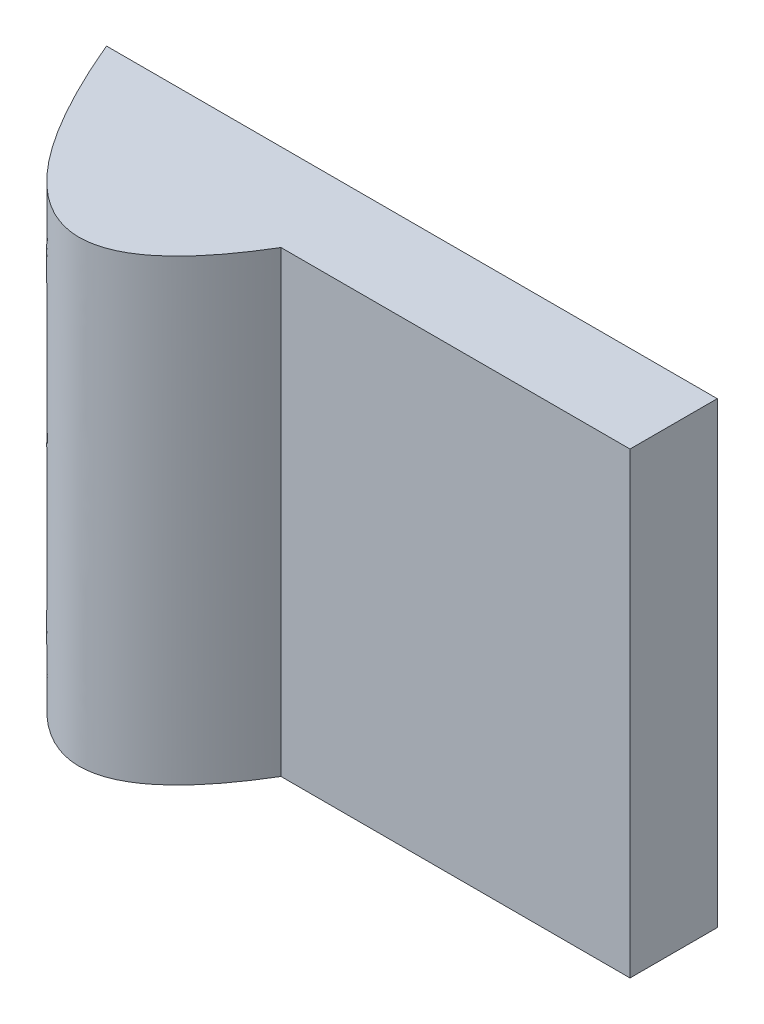
SolidWorks part; units mm, degrees
ref_plane "Alzado" through (0, 0, 0) normal (0, 0, 1) x (1, 0, 0)
ref_plane "Planta" through (0, 0, 0) normal (0, 1, 0) x (1, 0, 0)
ref_plane "Vista lateral" through (0, 0, 0) normal (1, 0, 0) x (0, 0, -1)
sketch "Croquis2" plane through (0, 0, 0) normal (0, 1, 0) x (1, 0, 0)
  line L0 (-200, 70) -> (200, 70)
  line L1 (-200, 70) -> (-200, -70)
  line L2 (-200, -70) -> (200, -70)
  line L3 (200, 70) -> (200, -70)
  line L4 (0, 70) -> (60, 70)
  line L5 (0, 70) -> (0, -70)
  line L6 (0, -70) -> (60, -70)
  line L7 (60, 70) -> (60, -70)
  line L8 (200, 70) -> (120, 70)
  line L9 (200, 70) -> (200, 50)
  line L10 (200, 50) -> (120, 50)
  line L11 (0, 70) -> (-60, 70)
  line L12 (0, 70) -> (0, 50)
  line L13 (0, 50) -> (-60, 50)
  line L14 (-60, 60.1561) -> (-60, 50)
  spline S0 degree 2 poles (60, 70) (89.7639, -0.5628) (120, 50) knots 0 0 0 1 1 1
  spline S1 degree 2 poles (-120, 70) (-89.7132, -0.7337) (-60, 50) knots 0 0 0 1 1 1
  point P14 (99.6856, 29.6804)
  point P15 (60, 70)
  point P16 (120, 50)
  point P18 (-120, 70)
  point P19 (-60, 50)
  point P20 (-79.8536, 29.6804)
extrude "Saliente-Extruir1" add sketch "Croquis2" along normal blind 105 contours L0 S0 L10 L3
sketch "Croquis4" plane through (0, 105, 0) normal (0, 1, 0) x (1, 0, 0)
  line L6 (197.5, 67.5) -> (63.8008, 67.5)
  line L7 (118.5717, 52.5) -> (197.5, 52.5)
  line L8 (197.5, 52.5) -> (197.5, 67.5)
  line L9 (197.5, 67.5) -> (63.8008, 67.5)
  line L10 (118.5717, 52.5) -> (197.5, 52.5)
  line L11 (197.5, 52.5) -> (197.5, 67.5)
  spline S0 degree 3 poles (-3596.0945, -1466.7295) (177.7786, 541.9769) (-14.1069, 219.5042) (69.7521, 55.1626) (71.4022, 52.1736) (74.1046, 47.8237) (75.0438, 46.3963) (77.0249, 43.6019) (78.0663, 42.2346) (79.7389, 40.2485) (80.3162, 39.5964) (81.5044, 38.3325) (82.1164, 37.7194) (83.3842, 36.5394) (84.04, 35.9724) (85.4075, 34.8973) (86.1149, 34.3929) (87.5736, 33.4767) (88.3267, 33.0632) (89.5018, 32.5283) (89.9011, 32.3643) (90.7172, 32.069) (91.1364, 31.9371) (92.4035, 31.6035) (93.2583, 31.4635) (94.5568, 31.3887) (94.9923, 31.3862) (95.8691, 31.4281) (96.3037, 31.4721) (97.5914, 31.6681) (98.431, 31.8842) (99.6662, 32.318) (100.0742, 32.4813) (100.8692, 32.8352) (101.2582, 33.0265) (102.4028, 33.6375) (103.1362, 34.0942) (104.2014, 34.8375) (104.5507, 35.095) (105.2386, 35.6276) (105.5777, 35.903) (107.2355, 37.3076) (108.456, 38.5261) (110.7628, 41.0837) (111.8478, 42.4239) (113.9208, 45.1913) (114.9086, 46.6196) (187.7154, 158.5348) (20.3329, 421.5127) (3671.0301, -1749.468) knots -6.49535 -6.49535 -6.49535 -6.49535 0.125 0.125 0.25 0.25 0.3125 0.3125 0.375 0.375 0.40625 0.40625 0.4375 0.4375 0.46875 0.46875 0.5 0.5 0.53125 0.53125 0.546875 0.546875 0.5625 0.5625 0.59375 0.59375 0.609375 0.609375 0.625 0.625 0.65625 0.65625 0.671875 0.671875 0.6875 0.6875 0.71875 0.71875 0.734375 0.734375 0.75 0.75 0.8125 0.8125 0.875 0.875 0.9375 0.9375 5.692899 5.692899 5.692899 5.692899 only from (63.8008, 67.5) to (118.5717, 52.5)
  spline S1 degree 3 poles (63.8008, 67.5) (65.1878, 64.3564) (66.6441, 61.2535) (69.7521, 55.1626) (71.4022, 52.1736) (74.1046, 47.8237) (75.0438, 46.3963) (77.0249, 43.6019) (78.0663, 42.2346) (79.7389, 40.2485) (80.3162, 39.5964) (81.5044, 38.3325) (82.1164, 37.7194) (83.3842, 36.5394) (84.04, 35.9724) (85.4075, 34.8973) (86.1149, 34.3929) (87.5736, 33.4767) (88.3267, 33.0632) (89.5018, 32.5283) (89.9011, 32.3643) (90.7172, 32.069) (91.1364, 31.9371) (92.4035, 31.6035) (93.2583, 31.4635) (94.5568, 31.3887) (94.9923, 31.3862) (95.8691, 31.4281) (96.3037, 31.4721) (97.5914, 31.6681) (98.431, 31.8842) (99.6662, 32.318) (100.0742, 32.4813) (100.8692, 32.8352) (101.2582, 33.0265) (102.4028, 33.6375) (103.1362, 34.0942) (104.2014, 34.8375) (104.5507, 35.095) (105.2386, 35.6276) (105.5777, 35.903) (107.2355, 37.3076) (108.456, 38.5261) (110.7628, 41.0837) (111.8478, 42.4239) (113.9208, 45.1913) (114.9086, 46.6196) (116.7975, 49.5232) (117.7007, 51.0014) (118.5717, 52.5) knots 0 0 0 0 0.125 0.125 0.25 0.25 0.3125 0.3125 0.375 0.375 0.40625 0.40625 0.4375 0.4375 0.46875 0.46875 0.5 0.5 0.53125 0.53125 0.546875 0.546875 0.5625 0.5625 0.59375 0.59375 0.609375 0.609375 0.625 0.625 0.65625 0.65625 0.671875 0.671875 0.6875 0.6875 0.71875 0.71875 0.734375 0.734375 0.75 0.75 0.8125 0.8125 0.875 0.875 0.9375 0.9375 1 1 1 1
  dimension "D1" = 2.5
extrude "Cortar-Extruir2" cut sketch "Croquis4" against normal through all from offset 2.5
